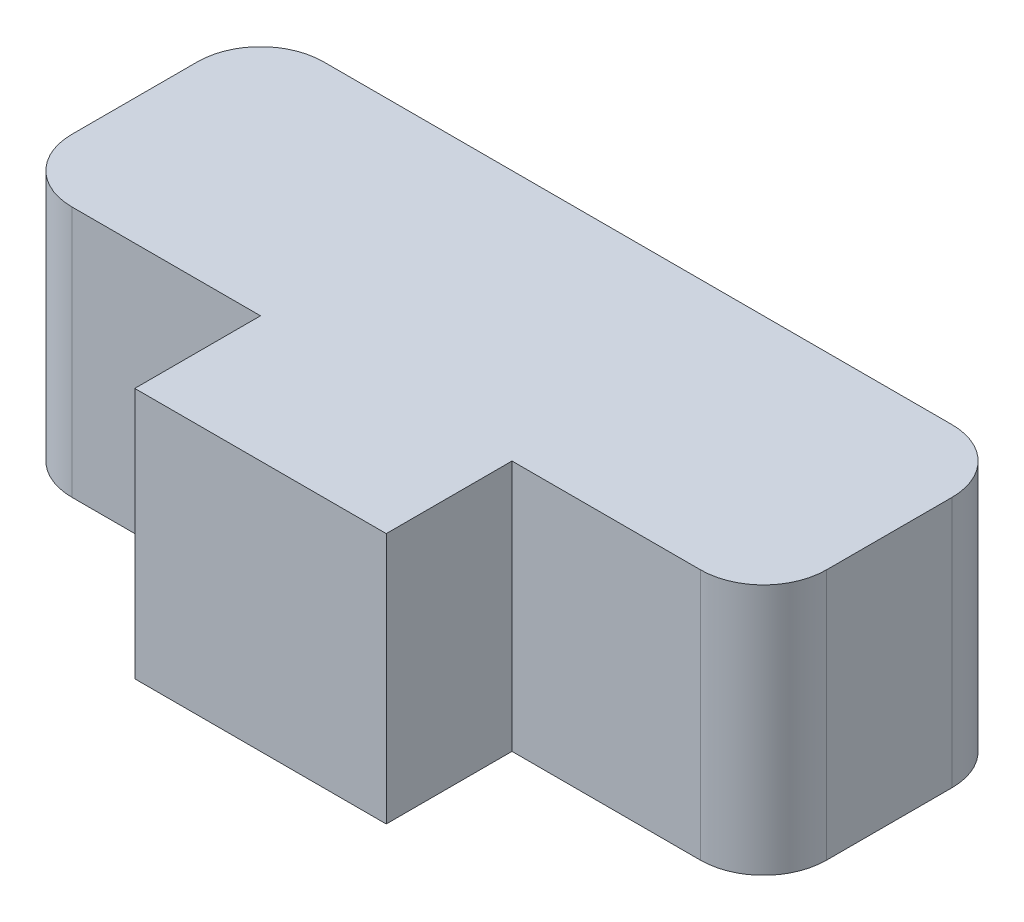
SolidWorks part; units mm, degrees
ref_plane "Front Plane" through (0, 0, 0) normal (0, 0, 1) x (1, 0, 0)
ref_plane "Top Plane" through (0, 0, 0) normal (0, 1, 0) x (1, 0, 0)
ref_plane "Right Plane" through (0, 0, 0) normal (1, 0, 0) x (0, 0, -1)
sketch "Sketch1" plane through (0, 0, 0) normal (0, 1, 0) x (1, 0, 0)
  line L0 (5.08, 0) -> (10.16, 0)
  line L1 (0, 0) -> (5.08, 0) construction
  line L2 (0, 0) -> (0, -2.54)
  line L3 (0, -2.54) -> (5.08, -2.54)
  line L4 (5.08, 0) -> (5.08, -2.54)
  line L5 (10.16, 0) -> (10.16, 5.08)
  line L6 (10.16, 5.08) -> (-5.08, 5.08)
  line L7 (-5.08, 5.08) -> (-5.08, 0)
  line L8 (-5.08, 0) -> (0, 0)
  dimension "D1" = 5.08
  dimension "D2" = 2.54
  dimension "D3" = 15.24
  dimension "D4" = 5.08
extrude "Boss-Extrude1" add sketch "Sketch1" along normal blind 5.08
fillet "Fillet1" radius 1.27 4 edges at (-5.08, 2.54, -5.08) (-5.08, 2.54, 0) (10.16, 2.54, -5.08) (10.16, 2.54, 0)
